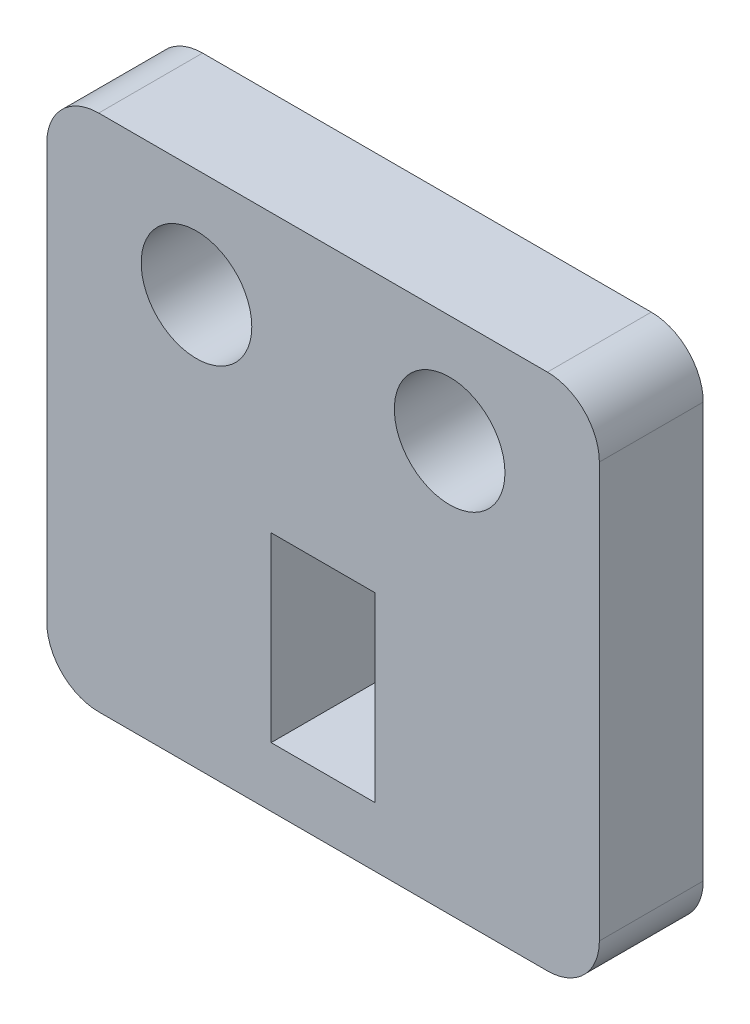
SolidWorks part; units mm, degrees
ref_plane "Plan de face" through (0, 0, 0) normal (0, 0, 1) x (1, 0, 0)
ref_plane "Plan de dessus" through (0, 0, 0) normal (0, 1, 0) x (1, 0, 0)
ref_plane "Plan de droite" through (0, 0, 0) normal (1, 0, 0) x (0, 0, -1)
sketch "Esquisse1" plane through (0, 0, 0) normal (0, 0, 1) x (1, 0, 0)
  line L0 (10.641, 19.9741) -> (10.641, 0) construction
  line L1 (0, 0) -> (21.282, 0)
  line L2 (0, 0) -> (0, 19.9741)
  line L3 (0, 19.9741) -> (21.282, 19.9741)
  line L4 (21.282, 0) -> (21.282, 19.9741)
  line L6 (8.641, 2.2941) -> (12.641, 2.2941)
  line L7 (8.641, 2.2941) -> (8.641, 9.2941)
  line L8 (8.641, 9.2941) -> (12.641, 9.2941)
  line L9 (12.641, 2.2941) -> (12.641, 9.2941)
  line L10 (8.641, 2.2941) -> (12.641, 9.2941) construction
  line L11 (8.641, 9.2941) -> (12.641, 2.2941) construction
  circle A0 centre (5.766, 15.7941) radius 2.13
  circle A1 centre (15.516, 15.7941) radius 2.13
  point P17 (10.641, 5.7941)
  dimension "D2" = 4.26
  dimension "D1" = 9.75
  dimension "D3" = 4.18
  dimension "D4" = 4
  dimension "D5" = 7
  dimension "D6" = 10
extrude "Boss.-Extru.1" add sketch "Esquisse1" along normal blind 4
fillet "Congé1" radius 2 4 edges at (0, 19.9741, 2) (0, 0, 2) (21.282, 0, 2) (21.282, 19.9741, 2)
